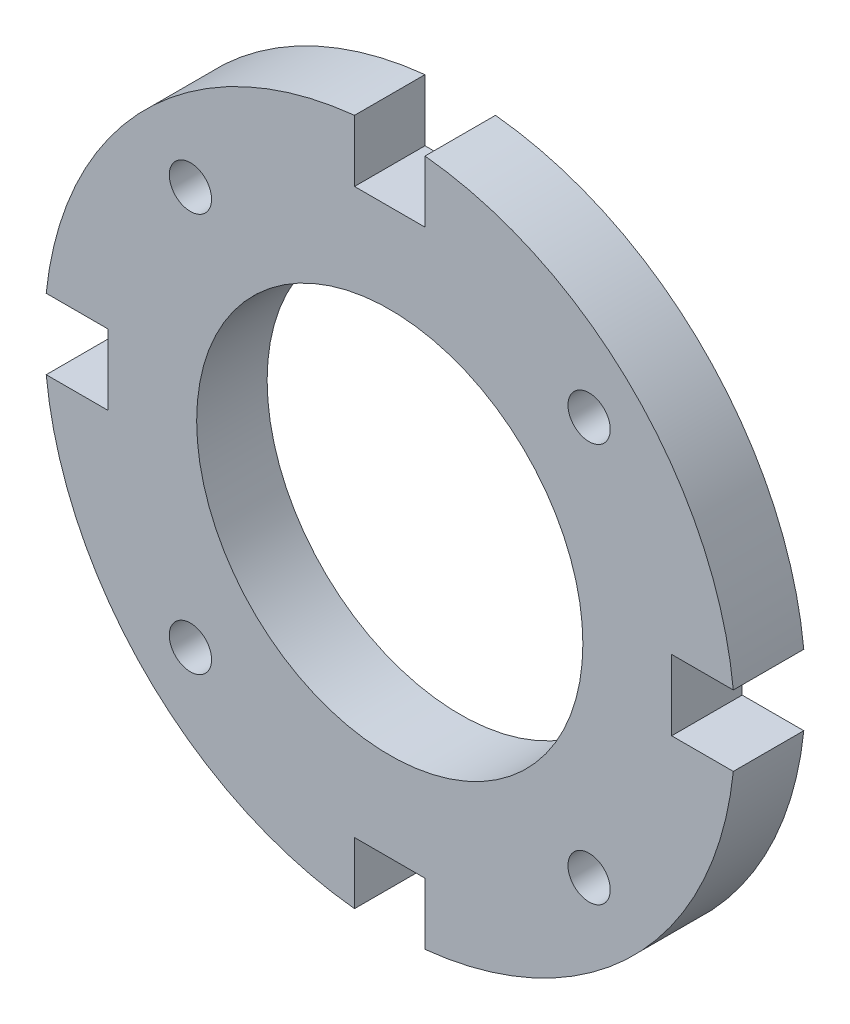
SolidWorks part; units mm, degrees
ref_plane "Plan de face" through (0, 0, 0) normal (0, 0, 1) x (1, 0, 0)
ref_plane "Plan de dessus" through (0, 0, 0) normal (0, 1, 0) x (1, 0, 0)
ref_plane "Plan de droite" through (0, 0, 0) normal (1, 0, 0) x (0, 0, -1)
sketch "Esquisse1" plane through (0, 0, 0) normal (0, 0, 1) x (1, 0, 0)
  line L0 (0, 0) -> (0, 31.2189) construction
  line L1 (0, 0) -> (37.7317, 0) construction
  line L2 (-2.5, 28.2406) -> (-2.5, -24.6241) construction
  line L3 (2.5, -24.6241) -> (2.5, 28.2406) construction
  line L4 (37.7317, 2.5) -> (-32.0453, 2.5) construction
  line L5 (-32.0453, -2.5) -> (37.7317, -2.5) construction
  line L6 (24.3721, 2.5) -> (20, 2.5)
  line L7 (20, 2.5) -> (20, -2.5)
  line L8 (20, -2.5) -> (24.3721, -2.5)
  line L9 (-24.3721, 2.5) -> (-20, 2.5)
  line L10 (-20, 2.5) -> (-20, -2.5)
  line L11 (-20, -2.5) -> (-24.3721, -2.5)
  line L12 (-2.5, -24.3721) -> (-2.5, -20)
  line L13 (-2.5, -20) -> (2.5, -20)
  line L14 (2.5, -20) -> (2.5, -24.3721)
  line L15 (2.5, 24.3721) -> (2.5, 20)
  line L16 (2.5, 20) -> (-2.5, 20)
  line L17 (-2.5, 20) -> (-2.5, 24.3721)
  line L18 (0, 0) -> (32.7248, 32.7248) construction
  line L19 (0, 0) -> (-36.0183, 36.0183) construction
  circle A0 centre (0, 0) radius 13.7
  circle A1 centre (0, 0) radius 24.5 construction
  arc A2 (2.5, 24.3721) -> (24.3721, 2.5) centre (0, 0) cw
  arc A3 (-2.5, 24.3721) -> (-24.3721, 2.5) centre (0, 0) ccw
  arc A4 (-24.3721, -2.5) -> (-2.5, -24.3721) centre (0, 0) ccw
  arc A5 (2.5, -24.3721) -> (24.3721, -2.5) centre (0, 0) ccw
  circle A6 centre (14.1421, 14.1421) radius 1.5
  circle A7 centre (14.1421, -14.1421) radius 1.5
  circle A8 centre (-14.1421, 14.1421) radius 1.5
  circle A9 centre (-14.1421, -14.1421) radius 1.5
  dimension "D1" = 27.4
  dimension "D2" = 49
  dimension "D5" = 40
  dimension "D7" = 20
  dimension "D8" = 3
  dimension "D3" = 5
  dimension "D4" = 5
  dimension "D6" = 45
extrude "Boss.-Extru.1" add sketch "Esquisse1" along normal blind 5
